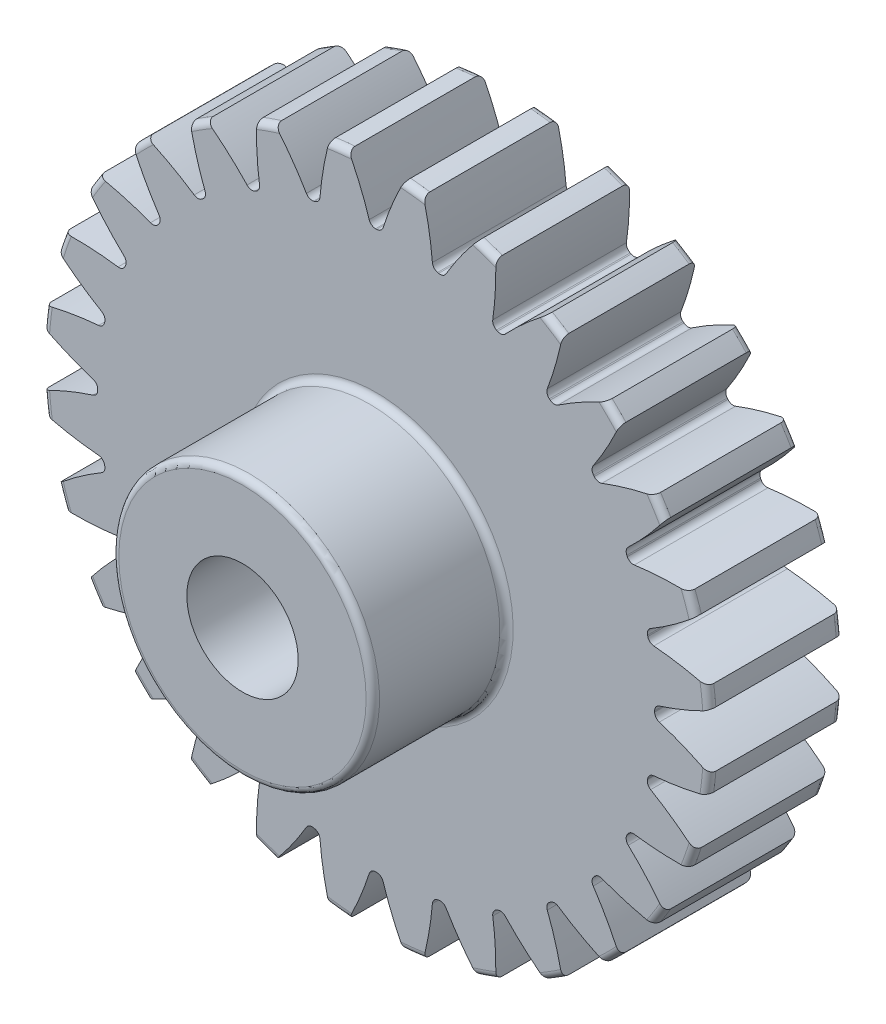
SolidWorks part; units mm, degrees
ref_plane "Front Plane" through (0, 0, 0) normal (0, 0, 1) x (1, 0, 0)
ref_plane "Top Plane" through (0, 0, 0) normal (0, 1, 0) x (1, 0, 0)
ref_plane "Right Plane" through (0, 0, 0) normal (1, 0, 0) x (0, 0, -1)
sketch "Sketch1" plane through (0, 0, 0) normal (0, 0, 1) x (1, 0, 0)
  line L0 (-355.6, 0) -> (355.6, 0) construction
  circle A0 centre (0, 0) radius 15 construction
  circle A1 centre (0, 0) radius 14 construction
  circle A2 centre (0, 0) radius 12.5 construction
  circle A3 centre (0, 0) radius 5.85 construction
  circle A4 centre (0, 0) radius 2.5 construction
  dimension "D1" = 2.5
  dimension "OD" = 30
  dimension "Pitch Dia." = 28
  dimension "D2" = 1
  dimension "D3" = 2.5
  dimension "Root Dia." = 25
  dimension "Hub Dia." = 11.7
  dimension "Shaft Dia." = 5
  dimension "Number of Teeth" = 711.2
sketch "Sketch2" plane through (0, 0, 0) normal (1, 0, 0) x (0, 0, -1)
  line L0 (0, 0) -> (-6, 0) construction
  line L1 (-6, 0) -> (-12, 0) construction
  dimension "Overall Width" = 12
  dimension "Face Width" = 6
sketch "Sketch4" plane through (0, 0, 0) normal (1, 0, 0) x (0, 0, -1)
  line L0 (-12, 2.5) -> (-12, 5.85)
  line L1 (-12, 5.85) -> (-6, 5.85)
  line L2 (-6, 5.85) -> (-6, 15)
  line L3 (-6, 15) -> (0, 15)
  line L4 (0, 15) -> (0, 2.5)
  line L5 (-6, 5.85) -> (-6, 0) construction
  line L6 (0, 15) -> (0, -15) construction
  line L7 (-6, 5.85) -> (0, 5.85) construction
  line L12 (-12, 2.5) -> (0, 2.5)
revolve "Revolve1" add sketch "Sketch4" angle 360 about L1
fillet "Fillet2" radius 0.3 4 edges at (0, 5.85, 12) (0, 5.85, 6) (0, 15, 6) (0, 15, 0)
sketch "Sketch7" plane through (0, 0, 6) normal (0, 0, 1) x (1, 0, 0)
  line L0 (0, 0) -> (0, 15) construction
  line L1 (0.785, 13.978) -> (1.2026, 14.9517) construction
  line L3 (1.6795, 14.9057) -> (1.5675, 13.912) construction
  line L4 (1.5675, 13.912) -> (1.3996, 12.4214) construction
  line L5 (0, 0) -> (1.3996, 12.4214) construction
  line L6 (0.785, 13.978) -> (0, 0) construction
  line L7 (0.785, 13.978) -> (0.8411, 14.9764) construction
  line L8 (0.785, 13.978) -> (0, 0) construction
  circle A0 centre (0, 0) radius 15 construction
  arc A1 (-0.0255, 12.5) -> (0.0255, 12.5) centre (0, 0) cw
  circle A2 centre (0, 0) radius 12.5 construction
  arc A3 (-0.785, 13.978) -> (0.785, 13.978) centre (0, 0) cw construction
  circle A4 centre (0, 0) radius 14 construction
  arc A5 (2.1116, 14.8506) -> (1.2459, 14.9482) centre (0, 0) ccw construction
  arc A6 (0.785, 13.978) -> (2.3451, 13.8022) centre (0, 0) cw construction
  arc A7 (-1.2459, 14.9482) -> (1.2459, 14.9482) centre (0, 0) cw
  arc A8 (0.312, 12.7089) -> (1.2459, 14.9482) centre (13.6515, 8.4596) cw
  arc A9 (-0.312, 12.7089) -> (-1.2459, 14.9482) centre (-13.6515, 8.4596) ccw
  arc A10 (-0.0255, 12.5) -> (-0.312, 12.7089) centre (-0.0261, 12.8) cw
  arc A11 (0.0255, 12.5) -> (0.312, 12.7089) centre (0.0261, 12.8) ccw
  point P26 (-0.2465, 12.4976)
  point P29 (0.2465, 12.4976)
  dimension "D4" = 0.3
  dimension "D5" = 14
  dimension "D2" = 1.5708
  dimension "D1" = 3.1416
  dimension "D3" = 20
extrude "Cut-Extrude2" cut sketch "Sketch7" against normal through all
pattern_circular "CirPattern1" count 28 over 360 about axis through (0, 0, 0) along (0, 0, 1) of "Cut-Extrude2"
equation "\"D1@Sketch1\"=2.5*(\"Pitch Dia.@Sketch1\"/\"Number of Teeth@Sketch1\")"
equation "\"D1@CirPattern1\"=\"Number of Teeth@Sketch1\""
equation "\"D1@Fillet2\"=\"OD@Sketch1\"*.01"
equation "\"D1@Sketch7\"=3.14159*(\"Pitch Dia.@Sketch1\"/\"Number of Teeth@Sketch1\")"
equation "\"D2@Sketch7\"=\"D1@Sketch7\"/2"
equation "\"D4@Sketch7\"=\"D1@Sketch7\"*.0955"
equation "\"D5@Sketch7\"=\"Pitch Dia.@Sketch1\"/2"
